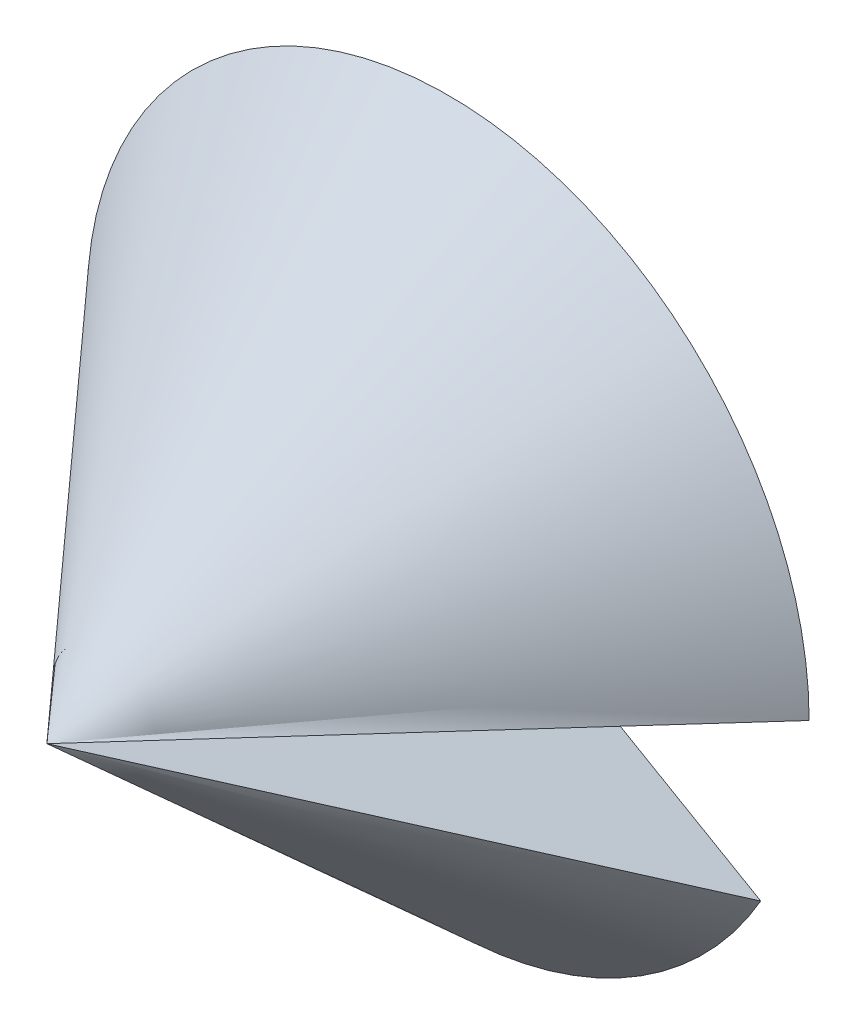
SolidWorks part; units mm, degrees
ref_plane "Front Plane" through (0, 0, 0) normal (0, 0, 1) x (1, 0, 0)
ref_plane "Top Plane" through (0, 0, 0) normal (0, 1, 0) x (1, 0, 0)
ref_plane "Right Plane" through (0, 0, 0) normal (1, 0, 0) x (0, 0, -1)
sketch "Sketch1" plane through (0, 0, 0) normal (0, 0, 1) x (1, 0, 0)
  circle A0 centre (0, 0) radius 45
  circle A1 centre (0, 0) radius 2
sketch "Sketch4" plane through (0, 0, 0) normal (0, 1, 0) x (1, 0, 0)
  line L0 (0, 0) -> (0, -50)
  line L1 (-45, 0) -> (45, 0) construction
  line L2 (0, -49.5) -> (0, 49.5) construction
  line L3 (0, -50) -> (45, 0)
  line L4 (-49.5, 0) -> (49.5, 0) construction
  line L5 (45, 0) -> (0, 0)
revolve "Revolve3" add sketch "Sketch4" angle 330 about L0
sketch "Sketch7" plane through (0, 0, 0) normal (0, 1, 0) x (1, 0, 0)
  line L0 (0, -50) -> (23.7196, 0)
  line L1 (0, -27.5) -> (0, 27.5) construction
  line L2 (0, -50) -> (38.9711, 0) construction
  line L3 (-49.5, 0) -> (49.5, 0) construction
  line L4 (17.4056, 0) -> (0, 0)
  line L5 (0, 0) -> (0, -50)
  line L6 (23.7196, 0) -> (17.4056, 0)
revolve "Revolve7" add sketch "Sketch7" angle 30 about L5
extrude "Cut-Extrude2" cut sketch "Sketch1" along normal blind 10 contours A1
